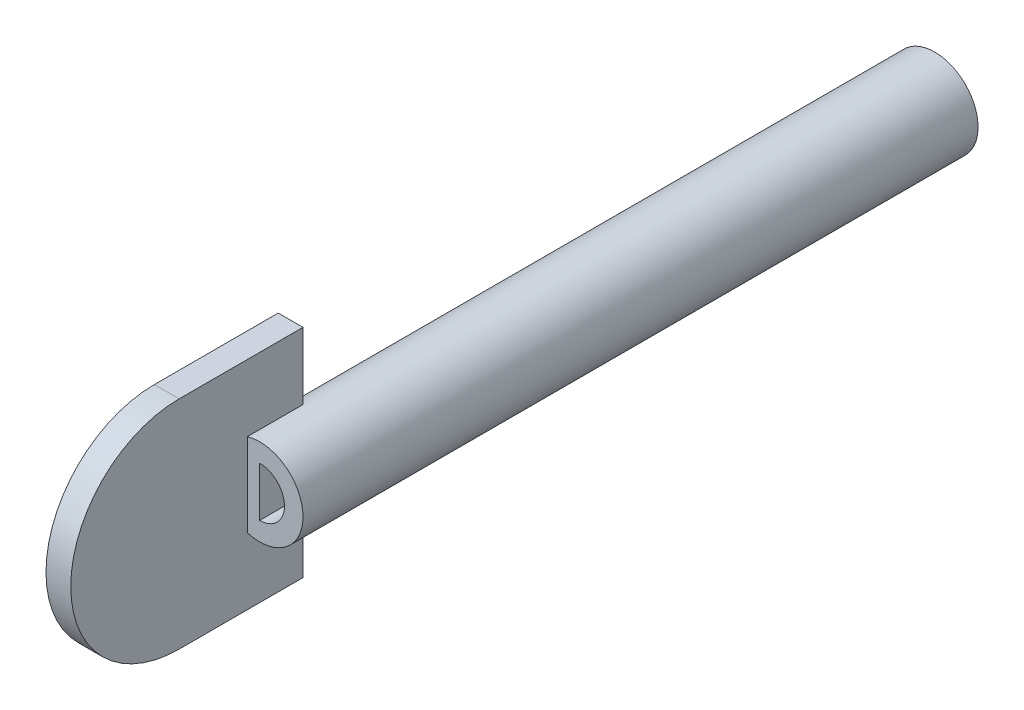
SolidWorks part; units mm, degrees
ref_plane "Plan de face" through (0, 0, 0) normal (0, 0, 1) x (1, 0, 0)
ref_plane "Plan de dessus" through (0, 0, 0) normal (0, 1, 0) x (1, 0, 0)
ref_plane "Plan de droite" through (0, 0, 0) normal (1, 0, 0) x (0, 0, -1)
sketch "Esquisse1" plane through (0, 0, 0) normal (1, 0, 0) x (0, 0, -1)
  line L1 (-20, 17.5) -> (20, 17.5)
  line L2 (-20, 17.5) -> (-20, -17.5)
  line L3 (-20, -17.5) -> (20, -17.5)
  line L4 (20, 17.5) -> (20, -17.5)
  line L5 (-20, 17.5) -> (20, -17.5) construction
  line L6 (-20, -17.5) -> (20, 17.5) construction
  point P0 (0, 0)
  dimension "D1" = 40
  dimension "D2" = 35
extrude "Boss.-Extru.1" add sketch "Esquisse1" along normal blind 4
sketch "Esquisse2" plane through (0, 0, 0) normal (-1, 0, 0) x (0, 0, 1)
  circle A0 centre (0, 0) radius 10
  dimension "D1" = 20
extrude "Enlèv. mat.-Extru.1" cut sketch "Esquisse2" against normal blind 2
sketch "Esquisse3" plane through (0, 0, 0) normal (-1, 0, 0) x (0, 0, 1)
  line L0 (-20, 17.5) -> (20, 17.5) construction
  line L1 (20, -17.5) -> (-20, -17.5) construction
  line L2 (0, -17.5) -> (20, -17.5)
  line L3 (20, -17.5) -> (20, 17.5)
  line L4 (20, 17.5) -> (0, 17.5)
  arc A0 (0, 17.5) -> (0, -17.5) centre (0, 0) cw
extrude "Enlèv. mat.-Extru.2" cut sketch "Esquisse3" against normal through all
sketch "Esquisse4" plane through (0, 0, -20) normal (0, 0, -1) x (-1, 0, 0)
  line L0 (-4, 0) -> (-6, 0) construction
  line L1 (-4, -17.5) -> (-4, 17.5) construction
  circle A0 centre (-6, 0) radius 7
  dimension "D2" = 14
  dimension "D1" = 2
extrude "Boss.-Extru.2" add sketch "Esquisse4" along normal blind 100 and the other way blind 9
sketch "Esquisse5" plane through (0, 0, -120) normal (0, 0, -1) x (-1, 0, 0)
  circle A0 centre (-6, 0) radius 6
  dimension "D1" = 12
extrude "Enlèv. mat.-Extru.5" cut sketch "Esquisse5" against normal blind 99
sketch "Esquisse9" plane through (0, 0, -11) normal (0, 0, 1) x (1, 0, 0)
  line L0 (4, 6.7082) -> (4, -6.7082)
  line L2 (4, 6.7082) -> (4, -6.7082)
  line L3 (4, 6.7082) -> (4, -6.7082)
  arc A1 (4, -6.7082) -> (4, 6.7082) centre (6, 0) ccw
  dimension "D1" = 0
sketch "Esquisse10" plane through (0, 0, -11) normal (0, 0, 1) x (1, 0, 0)
  line L0 (-1, 0) -> (13, 0) construction
  line L1 (13, 0) -> (6, 7) construction
  line L2 (6, 7) -> (6, -7) construction
  line L3 (6, -4) -> (6, 4)
  arc A0 (0, 3.6056) -> (0, -3.6056) centre (6, 0) ccw construction
  arc A1 (4, -6.7082) -> (4, 6.7082) centre (6, 0) ccw construction
  arc A2 (6, 4) -> (6, -4) centre (6, 0) cw
extrude "Enlèv. mat.-Extru.9" cut sketch "Esquisse10" against normal blind 99
